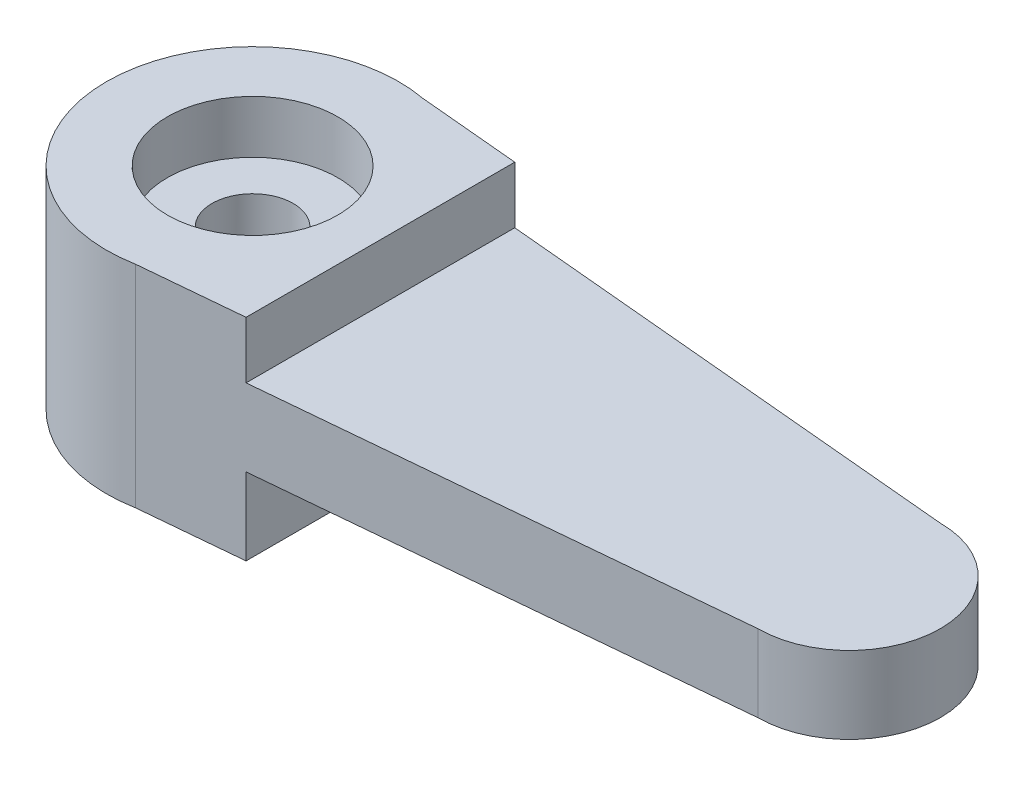
SolidWorks part; units mm, degrees
ref_plane "Alzado" through (0, 0, 0) normal (0, 0, 1) x (1, 0, 0)
ref_plane "Planta" through (0, 0, 0) normal (0, 1, 0) x (1, 0, 0)
ref_plane "Vista lateral" through (0, 0, 0) normal (1, 0, 0) x (0, 0, -1)
sketch "Croquis1" plane through (0, 0, 0) normal (0, 1, 0) x (1, 0, 0)
  line L0 (0, 0) -> (14.7, 0) construction
  line L1 (0, 3.6) -> (14.7, 2.25)
  line L6 (0, -3.6) -> (14.7, -2.25)
  circle A0 centre (0, 0) radius 3.6
  circle A2 centre (14.7, 0) radius 2.25
  point P3 (8.75, 0)
  dimension "D1" = 7.2
  dimension "D2" = 14.7
  dimension "D3" = 4.5
extrude "Saliente-Extruir2" add sketch "Croquis1" along normal mid plane 5.2
sketch3d "Croquis3D1"
  point P0 (0.039, 2.6, -1.873)
ref_plane "Plano1" through (0, 2.6, 0) normal (0, 1, 0) x (1, 0, 0)
sketch "Croquis3" plane through (0, 2.6, 0) normal (0, 1, 0) x (1, 0, 0)
  circle A0 centre (0, 0) radius 2.1
  dimension "D1" = 4.2
extrude "Cortar-Extruir1" cut sketch "Croquis3" against normal blind 1.3
sketch3d "Croquis3D2"
  point P0 (0.6309, 1.3, 0.039)
sketch3d "Croquis3D3"
  point P0 (-0.8323, 1.3, -0.2926)
ref_plane "Plano3" through (0, 1.3, 0) normal (0, 1, 0) x (1, 0, 0)
sketch "Croquis5" plane through (0, 1.3, 0) normal (0, 1, 0) x (1, 0, 0)
  circle A0 centre (0, 0) radius 1
  dimension "D1" = 2
extrude "Cortar-Extruir2" cut sketch "Croquis5" against normal blind 5 contours A0
sketch3d "Croquis3D4"
  point P0 (-1.5622, -2.6, -0.5879)
ref_plane "Plano4" through (0, -2.6, 0) normal (0, -1, 0) x (1, 0, 0)
sketch "Croquis6" plane through (0, -2.6, 0) normal (0, -1, 0) x (1, 0, 0)
  circle A0 centre (0, 0) radius 2.1
  dimension "D1" = 4.2
extrude "Cortar-Extruir3" cut sketch "Croquis6" against normal blind 2.8 contours A0
sketch "Croquis7" plane through (0, 0, 0) normal (0, 0, 1) x (1, 0, 0)
  line L1 (16.95, -2.6) -> (3.15, -2.6)
  line L2 (16.95, -2.6) -> (16.95, -0.7)
  line L3 (16.95, -0.7) -> (3.15, -0.7)
  line L4 (3.15, -2.6) -> (3.15, -0.7)
  dimension "D1" = 13.8
  dimension "D2" = 1.9
extrude "Cortar-Extruir4" cut sketch "Croquis7" against normal mid plane 10
sketch "Croquis10" plane through (0, 0, 0) normal (0, 0, 1) x (1, 0, 0)
  line L1 (3.15, 1.1999) -> (16.95, 1.1999)
  line L2 (3.15, 1.1999) -> (3.15, 3.3499)
  line L3 (3.15, 3.3499) -> (16.95, 3.3499)
  line L4 (16.95, 1.1999) -> (16.95, 3.3499)
  line L5 (3.15, -0.7) -> (3.15, 6.2035) construction
  point P8 (3.15, 2.2749)
  dimension "D1" = 13.8
  dimension "D2" = 2.15
extrude "Cortar-Extruir6" cut sketch "Croquis10" against normal mid plane 10
